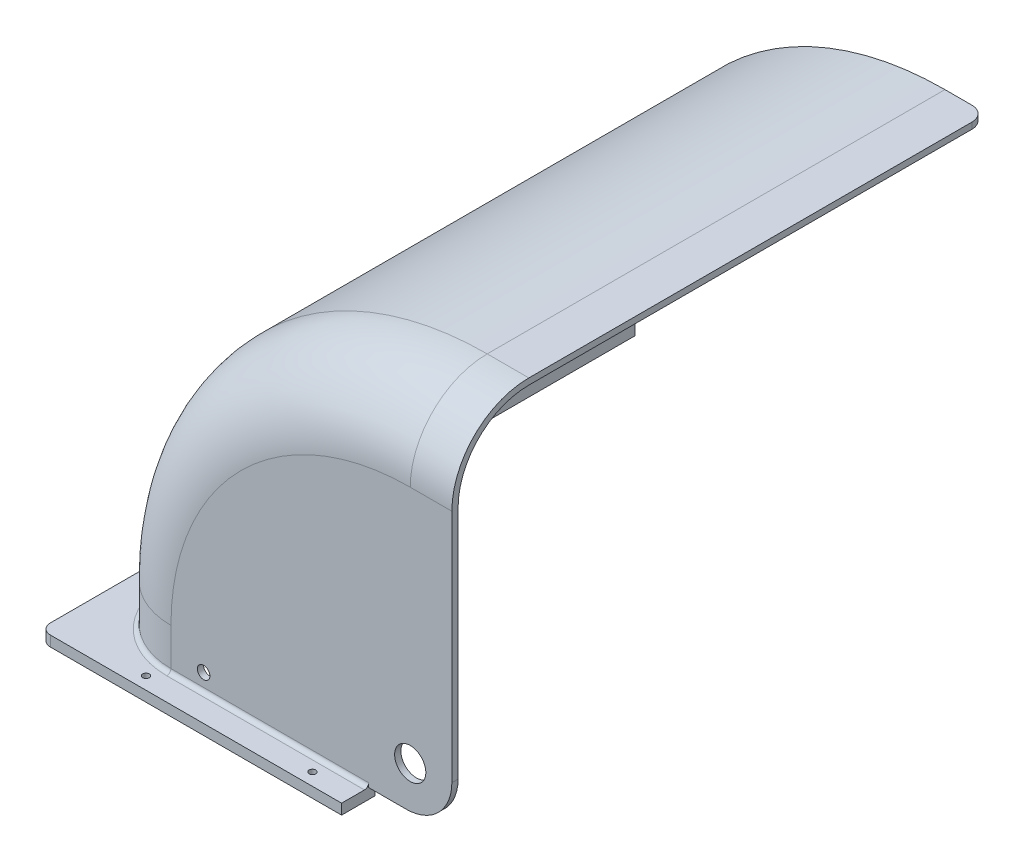
SolidWorks part; units mm, degrees
ref_plane "Front Plane" through (0, 0, 0) normal (0, 0, 1) x (1, 0, 0)
ref_plane "Top Plane" through (0, 0, 0) normal (0, 1, 0) x (1, 0, 0)
ref_plane "Right Plane" through (0, 0, 0) normal (1, 0, 0) x (0, 0, -1)
sketch "Sketch1" plane through (0, 0, 0) normal (0, 1, 0) x (1, 0, 0)
  line L0 (0, -254) -> (0, 254) construction
  line L2 (-165, 270) -> (-165, -270)
  line L5 (-165, 270) -> (0, 0) construction
  line L6 (-165, -270) -> (0, 0) construction
  line L9 (-149, -254) -> (-149, 254)
  line L11 (-149, 254) -> (0, 254)
  line L12 (-165, 270) -> (0, 270)
  line L21 (-149, -254) -> (0, -254)
  line L22 (-165, -270) -> (0, -270)
  line L23 (0, 254) -> (0, 270)
  line L24 (0, -254) -> (0, -270)
  line L25 (0, 270) -> (0, 264) construction
  line L26 (0, 264) -> (-40, 264) construction
  line L27 (-40, 264) -> (-120, 264) construction
  line L28 (-165, 0) -> (-159, 0) construction
  line L29 (-159, 0) -> (-159, 50) construction
  line L30 (-159, 50) -> (-159, 130) construction
  line L31 (0, 0) -> (-149, 0) construction
  line L32 (-159, 210) -> (-159, 50) construction
  line L33 (-40, -264) -> (-120, -264) construction
  line L34 (-159, -210) -> (-159, -50) construction
  line L35 (-159, -50) -> (-159, -130) construction
  circle A0 centre (-159, 130) radius 1.6
  circle A1 centre (-159, 50) radius 1.6
  circle A2 centre (-120, 264) radius 1.6
  circle A3 centre (-40, 264) radius 1.6
  circle A4 centre (-159, 210) radius 1.6
  circle A5 centre (-40, -264) radius 1.6
  circle A6 centre (-120, -264) radius 1.6
  circle A7 centre (-159, -210) radius 1.6
  circle A8 centre (-159, -50) radius 1.6
  circle A9 centre (-159, -130) radius 1.6
  point P0 (0, 0)
  point P9 (0, 0)
  point P26 (-159, 130)
  point P38 (-159, -130)
  dimension "D13" = 80
  dimension "D1" = 16
  dimension "D2" = 540
  dimension "D3" = 16
  dimension "D4" = 16
  dimension "D5" = 165
  dimension "D6" = 165
  dimension "D7" = 6
  dimension "D8" = 80
  dimension "D9" = 40
  dimension "D10" = 6
  dimension "D11" = 50
  dimension "D12" = 80
extrude "Boss-Extrude1" add sketch "Sketch1" along normal blind 5
sketch "Sketch12" plane through (0, 5, 0) normal (0, 1, 0) x (1, 0, 0)
  line L0 (0, -254) -> (-149, -254) construction
  line L1 (0, 254) -> (-149, 254)
  line L2 (0, 254) -> (0, -254) construction
  line L3 (0, -254) -> (-149, -254)
  line L4 (-149, 254) -> (-149, -254)
  line L5 (0, 257) -> (-152, 257)
  line L6 (-152, 257) -> (-152, -257)
  line L7 (0, -257) -> (-152, -257)
  line L8 (0, 257) -> (0, 254)
  line L9 (0, -257) -> (0, -254)
  dimension "D1" = 3
extrude "Boss-Extrude5" add sketch "Sketch12" along normal blind 20
fillet "Fillet8" radius 34 2 edges at (-149, 12.5, 254) (-149, 12.5, -254)
fillet "Fillet9" radius 37 2 edges at (-152, 15, -257) (-152, 15, 257)
sketch "Sketch13" plane through (0, 25, 0) normal (0, 1, 0) x (1, 0, 0)
  line L0 (0, 254) -> (-115, 254)
  line L1 (0, 257) -> (-115, 257)
  line L2 (0, 257) -> (0, -257) construction
  line L3 (0, -257) -> (-115, -257)
  line L4 (-152, 220) -> (-152, -220)
  line L5 (-149, 220) -> (-149, -220)
  line L6 (0, -254) -> (-115, -254)
  line L7 (0, 257) -> (0, 254)
  line L8 (0, -257) -> (0, -254)
  arc A0 (-115, 257) -> (-152, 220) centre (-115, 220) ccw
  arc A1 (-115, -257) -> (-152, -220) centre (-115, -220) cw
  arc A2 (-115, 254) -> (-149, 220) centre (-115, 220) ccw
  arc A3 (-115, -254) -> (-149, -220) centre (-115, -220) cw
  dimension "D3" = 37
  dimension "D4" = 37
  dimension "D1" = 152
  dimension "D2" = 514
  dimension "D5" = 3
revolve "Revolve4" add sketch "Sketch13" angle 90 about L2
sketch "Sketch15" plane through (0, 0, 0) normal (1, 0, 0) x (0, 0, -1)
  line L0 (-254, 5) -> (-254, 140)
  line L1 (-257, 5) -> (257, 5) construction
  line L2 (-257, 5) -> (-257, 140)
  line L3 (-220, 177) -> (220, 177)
  line L4 (257, 5) -> (257, 140)
  line L5 (-220, 174) -> (220, 174)
  line L6 (254, 5) -> (254, 140)
  line L7 (-257, 5) -> (-270, 5)
  line L8 (-270, 5) -> (-270, 0)
  line L9 (-270, 0) -> (-254, 0)
  line L10 (-254, 0) -> (-254, 5)
  line L11 (254, 5) -> (254, 0)
  line L12 (254, 0) -> (270, 0)
  line L13 (270, 0) -> (270, 5)
  line L14 (270, 5) -> (257, 5)
  arc A0 (-220, 177) -> (-257, 140) centre (-220, 140) ccw
  arc A1 (257, 140) -> (220, 177) centre (220, 140) ccw
  arc A2 (-220, 174) -> (-254, 140) centre (-220, 140) ccw
  arc A3 (254, 140) -> (220, 174) centre (220, 140) ccw
  dimension "D3" = 37
  dimension "D4" = 37
  dimension "D1" = 514
  dimension "D2" = 172
  dimension "D5" = 3
extrude "Boss-Extrude6" add sketch "Sketch15" along normal blind 20
sketch "Sketch16" plane through (0, 0, 270) normal (0, 0, 1) x (1, 0, 0)
  line L0 (-115, 5) -> (20, 5) construction
  line L1 (20, 0) -> (-20, 0)
  line L2 (20, 0) -> (20, 5)
  line L3 (20, 5) -> (-20, 5)
  line L4 (-20, 0) -> (-20, 5)
  dimension "D1" = 40
  dimension "D2" = 5
extrude "Cut-Extrude3" cut sketch "Sketch16" against normal up to surface (540 mm away) up to face at (-72.5, 2.5, -270)
fillet "Fillet10" radius 22 2 edges at (20, 5, 255.5) (20, 5, -255.5)
sketch "Sketch17" plane through (0, 0, 257) normal (0, 0, 1) x (1, 0, 0)
  line L0 (-115, 25) -> (20, 25) construction
  line L1 (20, 140) -> (20, 27) construction
  line L2 (0, 140) -> (0, 0) construction
  arc A0 (0, 140) -> (-115, 25) centre (0, 25) ccw construction
  circle A1 centre (0, 25) radius 7.5
  dimension "D1" = 25
extrude "Cut-Extrude4" cut sketch "Sketch17" against normal up to surface (514 mm away) up to face at (-33.0373, 52.323, -257)
fillet "Fillet11" radius 5 2 edges at (-165, 2.5, -270) (-165, 2.5, 270)
fillet "Fillet12" radius 2 5 edges at (-67.5, 5, -257) (-141.163, 5, -246.163) (-67.5, 5, 257) (-141.163, 5, 246.163) (-152, 5, 0)
sketch "Sketch18" plane through (0, 0, -257) normal (0, 0, -1) x (-1, 0, 0)
  line L0 (0, 25) -> (152, 7) construction
  line L1 (152, 25) -> (152, 7) construction
  line L2 (115, 7) -> (152, 7) construction
  line L3 (0, 25) -> (99.3061, 13.2401) construction
  circle A0 centre (99.3061, 13.2401) radius 3
  dimension "D2" = 6
  dimension "D1" = 100
extrude "Cut-Extrude5" cut sketch "Sketch18" against normal up to surface (514 mm away) up to face at (7.5, 25, 257)
sketch "Sketch19" plane through (0, 0, 0) normal (0, -1, 0) x (1, 0, 0)
  line L0 (0, 0) -> (20, 0) construction
  line L1 (0, 220) -> (0, -220) construction
  line L2 (20, 220) -> (20, -220) construction
  line L4 (20, 0) -> (-181.3065, 0)
  line L5 (20, 0) -> (20, -285.5378)
  line L6 (20, -285.5378) -> (-181.3065, -285.5378)
  line L7 (-181.3065, 0) -> (-181.3065, -285.5378)
extrude "Cut-Extrude6" cut sketch "Sketch19" against normal blind 269
fillet "Fillet13" radius 7 1 edges at (20, 175.5, 0)
